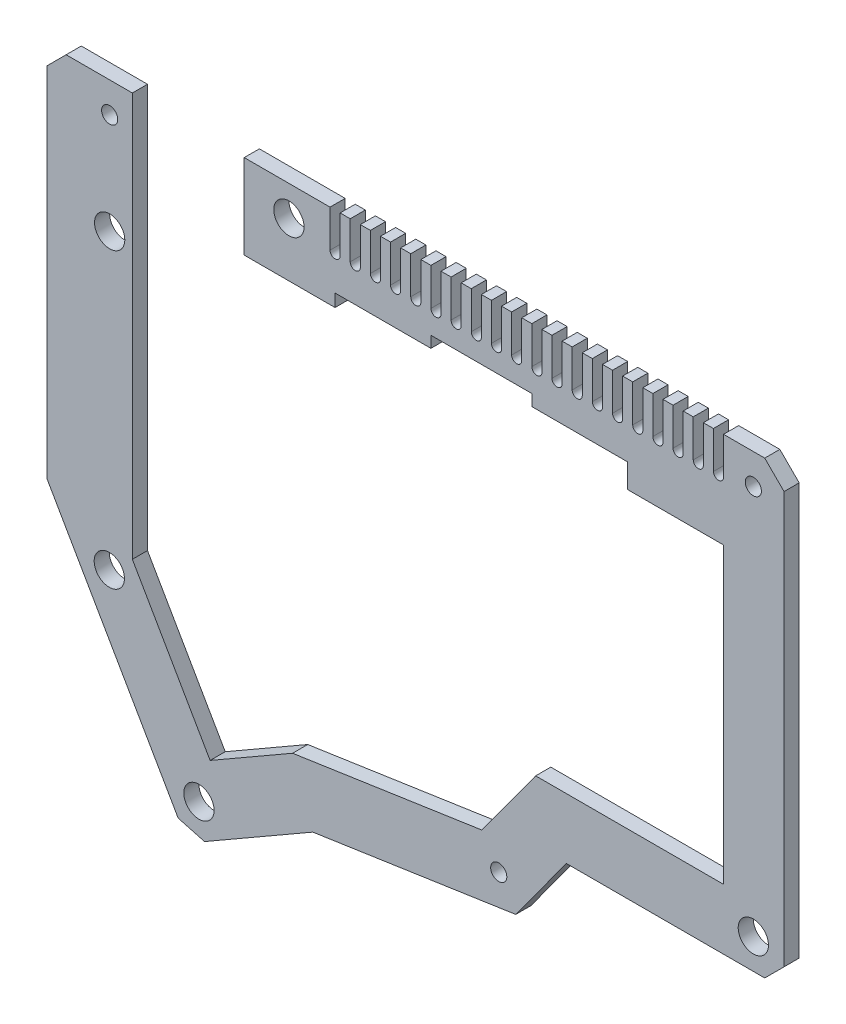
SolidWorks part; units mm, degrees
ref_plane "Plan de face" through (0, 0, 0) normal (0, 0, 1) x (1, 0, 0)
ref_plane "Plan de dessus" through (0, 0, 0) normal (0, 1, 0) x (1, 0, 0)
ref_plane "Plan de droite" through (0, 0, 0) normal (1, 0, 0) x (0, 0, -1)
sketch "Esquisse1" plane through (0, 0, 0) normal (0, 0, 1) x (1, 0, 0)
  line L0 (-117.3419, -15.4198) -> (-103.3409, -15.4198) construction
  line L1 (-103.3409, -15.4198) -> (-103.3409, -29.4208) construction
  line L2 (-103.3409, -29.4208) -> (-117.3419, -29.4208) construction
  line L3 (-117.3419, -29.4208) -> (-117.3419, -15.4198) construction
  line L4 (-98.3406, -27.0457) -> (-98.3406, -13.0447) construction
  line L5 (-98.3406, -13.0447) -> (-84.3396, -13.0447) construction
  line L6 (-84.3396, -13.0447) -> (-84.3396, -27.0457) construction
  line L7 (-84.3396, -27.0457) -> (-98.3406, -27.0457) construction
  line L8 (-79.3392, -24.6705) -> (-79.3392, -10.6695) construction
  line L9 (-79.3392, -10.6695) -> (-65.3382, -10.6695) construction
  line L10 (-65.3382, -10.6695) -> (-65.3382, -24.6705) construction
  line L11 (-65.3382, -24.6705) -> (-79.3392, -24.6705) construction
  line L12 (-60.3379, -27.0457) -> (-60.3379, -13.0447) construction
  line L13 (-60.3379, -13.0447) -> (-46.3369, -13.0447) construction
  line L14 (-46.3369, -13.0447) -> (-46.3369, -27.0457) construction
  line L15 (-46.3369, -27.0457) -> (-60.3379, -27.0457) construction
  line L16 (-41.3365, -31.796) -> (-41.3365, -17.795) construction
  line L17 (-41.3365, -17.795) -> (-27.3355, -17.795) construction
  line L18 (-27.3355, -17.795) -> (-27.3355, -31.796) construction
  line L19 (-27.3355, -31.796) -> (-41.3365, -31.796) construction
  line L20 (-22.3347, -31.796) -> (-22.3347, -17.795) construction
  line L21 (-22.3347, -17.795) -> (-8.3337, -17.795) construction
  line L22 (-8.3337, -17.795) -> (-8.3337, -31.796) construction
  line L23 (-8.3337, -31.796) -> (-22.3347, -31.796) construction
  line L24 (-117.3419, -34.4212) -> (-103.3409, -34.4212) construction
  line L25 (-103.3409, -34.4212) -> (-103.3409, -48.4222) construction
  line L26 (-103.3409, -48.4222) -> (-117.3419, -48.4222) construction
  line L27 (-117.3419, -48.4222) -> (-117.3419, -34.4212) construction
  line L28 (-98.3406, -32.046) -> (-84.3396, -32.046) construction
  line L29 (-84.3396, -32.046) -> (-84.3396, -46.047) construction
  line L30 (-84.3396, -46.047) -> (-98.3406, -46.047) construction
  line L31 (-98.3406, -46.047) -> (-98.3406, -32.046) construction
  line L32 (-79.3392, -29.6709) -> (-65.3382, -29.6709) construction
  line L33 (-65.3382, -29.6709) -> (-65.3382, -43.6718) construction
  line L34 (-65.3382, -43.6718) -> (-79.3392, -43.6718) construction
  line L35 (-79.3392, -43.6718) -> (-79.3392, -29.6709) construction
  line L36 (-60.3379, -32.046) -> (-46.3369, -32.046) construction
  line L37 (-46.3369, -32.046) -> (-46.3369, -46.047) construction
  line L38 (-46.3369, -46.047) -> (-60.3379, -46.047) construction
  line L39 (-60.3379, -46.047) -> (-60.3379, -32.046) construction
  line L40 (-41.3365, -36.7964) -> (-27.3355, -36.7964) construction
  line L41 (-27.3355, -36.7964) -> (-27.3355, -50.7973) construction
  line L42 (-27.3355, -50.7973) -> (-41.3365, -50.7973) construction
  line L43 (-41.3365, -50.7973) -> (-41.3365, -36.7964) construction
  line L44 (-22.3347, -36.7964) -> (-8.3337, -36.7964) construction
  line L45 (-8.3337, -36.7964) -> (-8.3337, -50.7973) construction
  line L46 (-8.3337, -50.7973) -> (-22.3347, -50.7973) construction
  line L47 (-22.3347, -50.7973) -> (-22.3347, -36.7964) construction
  line L48 (-22.3347, -55.7977) -> (-8.3337, -55.7977) construction
  line L49 (-8.3337, -55.7977) -> (-8.3337, -69.7987) construction
  line L50 (-8.3337, -69.7987) -> (-22.3347, -69.7987) construction
  line L51 (-22.3347, -69.7987) -> (-22.3347, -55.7977) construction
  line L52 (-41.3365, -55.7977) -> (-27.3355, -55.7977) construction
  line L53 (-27.3355, -55.7977) -> (-27.3355, -69.7987) construction
  line L54 (-27.3355, -69.7987) -> (-41.3365, -69.7987) construction
  line L55 (-41.3365, -69.7987) -> (-41.3365, -55.7977) construction
  line L56 (-60.3379, -51.0474) -> (-46.3369, -51.0474) construction
  line L57 (-46.3369, -51.0474) -> (-46.3369, -65.0484) construction
  line L58 (-46.3369, -65.0484) -> (-60.3379, -65.0484) construction
  line L59 (-60.3379, -65.0484) -> (-60.3379, -51.0474) construction
  line L60 (-79.3392, -48.6722) -> (-65.3382, -48.6722) construction
  line L61 (-65.3382, -48.6722) -> (-65.3382, -62.6732) construction
  line L62 (-65.3382, -62.6732) -> (-79.3392, -62.6732) construction
  line L63 (-79.3392, -62.6732) -> (-79.3392, -48.6722) construction
  line L64 (-98.3406, -51.0474) -> (-84.3396, -51.0474) construction
  line L65 (-84.3396, -51.0474) -> (-84.3396, -65.0484) construction
  line L66 (-84.3396, -65.0484) -> (-98.3406, -65.0484) construction
  line L67 (-98.3406, -65.0484) -> (-98.3406, -51.0474) construction
  line L68 (-117.3419, -53.4225) -> (-103.3409, -53.4225) construction
  line L69 (-103.3409, -53.4225) -> (-103.3409, -67.4235) construction
  line L70 (-103.3409, -67.4235) -> (-117.3419, -67.4235) construction
  line L71 (-117.3419, -67.4235) -> (-117.3419, -53.4225) construction
  line L72 (-88.8399, -70.6738) -> (-74.8389, -70.6738) construction
  line L73 (-74.8389, -70.6738) -> (-74.8389, -84.6747) construction
  line L74 (-74.8389, -84.6747) -> (-88.8399, -84.6747) construction
  line L75 (-88.8399, -84.6747) -> (-88.8399, -70.6738) construction
  line L76 (-111.4175, -75.4665) -> (-97.8899, -71.8565) construction
  line L77 (-97.8899, -71.8565) -> (-94.28, -85.3841) construction
  line L78 (-94.28, -85.3841) -> (-107.8075, -88.9941) construction
  line L79 (-107.8075, -88.9941) -> (-111.4175, -75.4665) construction
  line L80 (-134.6581, -81.5997) -> (-122.5281, -74.6075) construction
  line L81 (-122.5281, -74.6075) -> (-115.5359, -86.7375) construction
  line L82 (-115.5359, -86.7375) -> (-127.6659, -93.7297) construction
  line L83 (-127.6659, -93.7297) -> (-134.6581, -81.5997) construction
  line L86 (-6.3391, -71.9336) -> (-62.0853, -71.9336) construction
  line L89 (-72.824, -86.6446) -> (-62.0853, -71.9336) construction
  line L96 (-109.7697, -91.4639) -> (-73.0906, -86.6918) construction
  line L97 (-124.664, -99.8297) -> (-110.3971, -91.5881) construction
  line L98 (-139.9408, -76.5013) -> (-126.7151, -99.4281) construction
  line L99 (-119.8527, -15.5421) -> (-139.6028, -15.5421) construction
  line L100 (-100.8528, -13.2921) -> (-118.8527, -13.2921) construction
  line L101 (-63.8455, -8.5421) -> (-80.8528, -8.5421) construction
  line L102 (-44.8455, -10.792) -> (-62.8485, -10.792) construction
  line L103 (-25.8456, -15.5421) -> (-43.8486, -15.5421) construction
  line L104 (-6.8456, -15.5421) -> (-23.8529, -15.5421) construction
  line L105 (-6.2741, -71.3672) -> (-6.2741, -16.1136) construction
  line L106 (-23.8529, -71.9423) -> (-6.8456, -71.9423) construction
  line L107 (-61.8455, -71.9423) -> (-25.8456, -71.9423) construction
  line L108 (-72.6738, -86.4911) -> (-62.1363, -72.0583) construction
  line L109 (-140.1743, -16.1136) -> (-140.1743, -75.5958) construction
  line L110 (-134.3462, 1.5705) -> (-134.3466, -55.7217) construction
  line L111 (-134.3466, -55.7217) -> (-160.479, -70.8411) construction
  line L112 (-160.479, -70.8411) -> (-133.7613, -117.344) construction
  line L113 (-126.937, -119.1852) -> (-105.0783, -106.604) construction
  line L114 (-105.0783, -106.604) -> (-64.4097, -100.5586) construction
  line L115 (-64.4097, -100.5586) -> (-54.4636, -86.9336) construction
  line L116 (3.6609, -86.9336) -> (-54.4636, -86.9336) construction
  line L117 (-10.3391, -81.9326) -> (-10.3391, 1.3161) construction
  line L122 (3.6609, 6.3153) -> (-96.3444, 6.3209) construction
  line L129 (8.6609, -86.9336) -> (8.6609, -0.6796) construction
  line L130 (-48.3431, 6.3182) -> (-96.3444, 6.3209) construction
  line L131 (-115.3458, 1.5705) -> (-134.3462, 1.5705) construction
  line L132 (-160.479, -3.4295) -> (-160.479, -70.8411) construction
  line L134 (-119.3463, 1.5705) -> (-119.3466, -64.3728) construction
  line L135 (-119.3466, -64.3728) -> (-135.695, -73.8315) construction
  line L136 (-140.0228, -71.3355) -> (-140.0228, 1.5705) construction
  line L138 (-160.479, -70.8411) -> (-131.2704, -121.6794) construction
  line L139 (-131.2704, -121.6794) -> (-105.0783, -106.604) construction
  line L140 (-133.7613, -117.344) -> (-126.937, -119.1852) construction
  line L142 (-10.3391, 1.3161) -> (-15.3391, 6.3163) construction
  line L143 (8.6609, -86.9336) -> (-54.4636, -86.9336) construction
  line L144 (-10.3391, -81.9326) -> (-15.3391, -86.9326) construction
  line L147 (-103.3409, 6.3209) -> (-96.3444, 6.3209) construction
  line L148 (-103.3409, 6.3209) -> (-119.3463, 6.3209) construction
  line L149 (-119.3463, 6.3209) -> (-119.3463, 1.5705) construction
  line L150 (-140.0228, 1.5705) -> (-140.0228, 6.3209) construction
  line L151 (-140.0228, 6.3209) -> (-155.479, 6.3209) construction
  line L152 (-160.479, 1.3209) -> (-160.479, -3.4295) construction
  line L153 (-155.479, 6.3209) -> (-160.479, 1.3209) construction
  line L154 (8.6609, -1.685) -> (-119.3463, -1.6779) construction
  line L155 (-146.0924, -79.8227) -> (-128.3223, -110.752) construction
  line L156 (-128.3223, -110.752) -> (-107.7547, -98.9139) construction
  line L157 (-140.0228, -78.3428) -> (-126.1111, -102.5565)
  line L158 (-126.1111, -102.5565) -> (-109.762, -93.1464)
  line L159 (-109.762, -93.1464) -> (-72.2631, -87.5722)
  line L160 (-72.2631, -87.5722) -> (-61.5772, -72.9336)
  line L162 (-24.3391, -72.9336) -> (-24.3391, -14.6796)
  line L164 (-43.3418, -14.6796) -> (-43.3418, -9.9293)
  line L165 (-43.3418, -9.9293) -> (-62.3431, -9.9293)
  line L166 (-62.3431, -9.9293) -> (-62.3431, -7.681)
  line L167 (-62.3431, -7.681) -> (-82.3444, -7.6799)
  line L168 (-82.3444, -7.6799) -> (-82.3444, -9.9293)
  line L169 (-82.3444, -9.9293) -> (-101.3458, -9.9293)
  line L170 (-101.3458, -9.9293) -> (-101.3458, -12.4295)
  line L171 (-101.3458, -12.4295) -> (-119.3464, -12.4295)
  line L172 (-120.3463, -12.4295) -> (-120.3466, -64.3728) construction
  line L173 (-119.8474, -63.5072) -> (-140.5236, -75.4699) construction
  line L174 (-107.7547, -98.9139) -> (-68.8973, -93.1378) construction
  line L175 (-68.8973, -93.1378) -> (-58.5285, -78.9336) construction
  line L176 (0.6609, -78.9336) -> (-58.5285, -78.9336) construction
  line L177 (-18.3391, -78.9336) -> (-18.3391, -1.6845) construction
  line L178 (-62.3428, -1.681) -> (-82.3441, -1.6799) construction
  line L179 (0.6609, -78.9336) -> (0.6609, -14.6796) construction
  line L180 (-146.0228, -76.3355) -> (-146.0228, 1.5705) construction
  line L181 (-140.0228, -76.3355) -> (-140.0228, 1.5705) construction
  line L182 (-135.695, -73.8315) -> (-140.0228, -71.3355) construction
  line L183 (-16.1687, 4.3164) -> (-96.3445, 4.3209)
  line L184 (-103.3409, 4.3209) -> (-96.3445, 4.3209)
  line L185 (-103.3409, 4.3209) -> (-119.3463, 4.3209)
  line L186 (-117.3463, 4.3209) -> (-117.3463, 1.5705) construction
  line L187 (-117.3463, 1.5705) -> (-117.3466, -65.5263) construction
  line L188 (-117.3466, -65.5263) -> (-135.6934, -76.1412) construction
  line L189 (-135.6934, -76.1412) -> (-142.0228, -72.4908) construction
  line L190 (-142.0228, -72.4908) -> (-142.0228, 1.5705) construction
  line L191 (-142.0228, 1.5705) -> (-142.0228, 4.3209) construction
  line L192 (-141.5228, 4.3209) -> (-154.6506, 4.3209)
  line L193 (-154.6506, 4.3209) -> (-158.479, 0.4924)
  line L194 (-158.479, 0.4924) -> (-158.479, -3.4295)
  line L195 (-158.479, -3.4295) -> (-158.479, -70.3075)
  line L196 (-158.479, -70.3075) -> (-132.44, -115.629)
  line L197 (-132.44, -115.629) -> (-127.2163, -117.0383)
  line L198 (-127.2163, -117.0383) -> (-105.7474, -104.6815)
  line L199 (-105.7474, -104.6815) -> (-65.5316, -98.7034)
  line L200 (-65.5316, -98.7034) -> (-55.4798, -84.9336)
  line L201 (-16.1675, -84.9336) -> (-55.4798, -84.9336)
  line L202 (-12.3391, -81.1052) -> (-16.1675, -84.9336)
  line L203 (-12.3391, -81.1052) -> (-12.3391, 0.4866)
  line L204 (-12.3391, 0.4866) -> (-16.1687, 4.3164)
  line L205 (-103.3409, 4.3209) -> (-117.3463, 4.3209) construction
  line L206 (-142.0228, 4.3209) -> (-154.6506, 4.3209) construction
  line L207 (-140.0228, 4.3209) -> (-140.0228, -75.1802) construction
  line L208 (-119.3463, 4.3209) -> (-119.3464, -12.4295)
  line L209 (-140.0228, -78.3428) -> (-140.8899, -76.8336)
  line L210 (-101.3458, -12.4295) -> (-120.3463, -12.4295) construction
  line L211 (-140.8899, -76.8336) -> (-126.1111, -102.5565) construction
  line L217 (-6.3391, -71.9336) -> (-6.3391, -15.6796) construction
  line L220 (-6.3391, -15.6796) -> (-44.3418, -15.6796) construction
  line L221 (-44.3418, -15.6796) -> (-44.3418, -10.9293) construction
  line L222 (-44.3418, -10.9293) -> (-63.3431, -10.9293) construction
  line L223 (-63.3431, -10.9293) -> (-63.3431, -8.681) construction
  line L224 (-63.3431, -8.681) -> (-81.3444, -8.68) construction
  line L225 (-81.3444, -8.68) -> (-81.3444, -10.9293) construction
  line L226 (-81.3444, -10.9293) -> (-100.3458, -10.9293) construction
  line L227 (-100.3458, -10.9293) -> (-100.3458, -13.4295) construction
  line L228 (-100.3458, -13.4295) -> (-119.3463, -13.4295) construction
  line L231 (-119.3463, -13.4295) -> (-119.3466, -64.3728) construction
  line L232 (-119.3466, -64.3728) -> (-140.0228, -76.3355) construction
  line L233 (-140.0228, -76.3355) -> (-125.7426, -101.1906) construction
  line L234 (-125.7426, -101.1906) -> (-110.0965, -92.1851) construction
  line L235 (-110.0965, -92.1851) -> (-72.824, -86.6446) construction
  line L236 (-141.5228, -75.732) -> (-140.8899, -76.8336)
  line L238 (-141.5228, 4.3209) -> (-141.5228, -75.1802)
  line L239 (-141.5228, -75.1802) -> (-141.5228, -75.732)
  line L240 (-5.3391, -72.9336) -> (-5.3391, -14.6796) construction
  line L241 (8.6609, -81.9336) -> (3.6609, -86.9336) construction
  line L242 (6.6609, -81.1052) -> (2.8325, -84.9336) construction
  line L243 (8.6609, -81.9336) -> (8.6609, 1.315) construction
  line L244 (6.6609, -81.1052) -> (6.6609, 0.4866) construction
  line L245 (8.6609, 1.315) -> (3.6609, 6.3153) construction
  line L246 (6.6609, 0.4866) -> (2.8324, 4.3153) construction
  line L247 (-24.3391, -14.6796) -> (-43.3418, -14.6796)
  line L248 (2.8324, 4.3153) -> (-96.3445, 4.3209) construction
  line L249 (-24.3391, -72.9336) -> (-61.5772, -72.9336)
  line L250 (-5.3391, -14.6796) -> (-43.3418, -14.6796) construction
  line L252 (-5.3391, -72.9336) -> (-61.5772, -72.9336) construction
  line L253 (2.8325, -84.9336) -> (-55.4798, -84.9336) construction
  line L328 (-48.3431, 4.0707) -> (-48.3431, 6.3182) construction
  line L329 (-29.3418, 4.0707) -> (-48.3431, 4.0707) construction
  line L330 (-29.3418, -0.6796) -> (-29.3418, 4.0707) construction
  line L331 (8.6609, -0.6796) -> (-29.3418, -0.6796) construction
  line L332 (-115.3458, 4.0707) -> (-115.3458, 1.5705) construction
  line L333 (-96.3444, 4.0707) -> (-115.3458, 4.0707) construction
  line L334 (-96.3444, 6.3209) -> (-96.3444, 4.0707) construction
  circle A2 centre (-18.3391, -1.6845) radius 1.6 construction
  circle A3 centre (-18.3391, -1.6845) radius 3 construction
  circle A4 centre (-110.3971, -1.6784) radius 1.6 construction
  circle A5 centre (-18.3391, -78.9336) radius 1.6 construction
  circle A6 centre (-68.8973, -93.1378) radius 1.6 construction
  circle A7 centre (-128.3223, -110.752) radius 1.6 construction
  circle A8 centre (-146.0924, -79.8227) radius 1.6 construction
  circle A9 centre (-146.0228, -1.6779) radius 1.6 construction
  point P138 (-160.479, 1.5705)
  point P139 (-10.3391, 6.3161)
  point P150 (-160.479, 6.3209)
  dimension "D3" = 3.2
  dimension "D4" = 6
  dimension "D6" = 3.2
  dimension "D7" = 3.2
  dimension "D8" = 3.2
  dimension "D9" = 3.2
  dimension "D10" = 3.2
  dimension "D15" = 3.2
  dimension "D2" = 6
  dimension "D1" = 15
  dimension "D5" = 1
  dimension "D13" = 6
  dimension "D16" = 2
  dimension "D17" = 1.5
extrude "Boss.-Extru.2" add sketch "Esquisse1" along normal blind 3
sketch "Esquisse2" plane through (0, 0, 3) normal (0, 0, 1) x (1, 0, 0)
  line L0 (-12.3391, -3.0693) -> (-25.3391, -3.0693) construction
  line L1 (-12.3391, -81.1052) -> (-12.3391, 0.4866) construction
  line L2 (-25.3391, -3.0693) -> (-25.3391, 4.3169) construction
  line L3 (-29.3391, 4.3169) -> (-29.3391, -3.0693) construction
  line L4 (-16.1687, 4.3164) -> (-96.3445, 4.3209) construction
  line L7 (-25.3391, 4.3169) -> (-25.3391, -3.0693) construction
  line L10 (-24.3391, 4.3169) -> (-24.3391, -3.0693)
  line L13 (-26.3391, 4.3169) -> (-26.3391, -3.0693)
  line L14 (-28.3391, 4.3169) -> (-28.3391, -3.0693)
  line L15 (-30.3391, 4.3169) -> (-30.3391, -3.0693)
  line L16 (-33.3391, 4.3169) -> (-33.3391, -3.0693) construction
  line L17 (-32.3391, 4.3169) -> (-32.3391, -3.0693)
  line L18 (-34.3391, 4.3169) -> (-34.3391, -3.0693)
  line L19 (-37.3391, 4.3169) -> (-37.3391, -3.0693) construction
  line L20 (-36.3391, 4.3169) -> (-36.3391, -3.0693)
  line L21 (-38.3391, 4.3169) -> (-38.3391, -3.0693)
  line L22 (-41.3391, 4.3169) -> (-41.3391, -3.0693) construction
  line L23 (-40.3391, 4.3169) -> (-40.3391, -3.0693)
  line L24 (-42.3391, 4.3169) -> (-42.3391, -3.0693)
  line L25 (-45.3391, 4.3169) -> (-45.3391, -3.0693) construction
  line L26 (-44.3391, 4.3169) -> (-44.3391, -3.0693)
  line L27 (-46.3391, 4.3169) -> (-46.3391, -3.0693)
  line L28 (-49.3391, 4.3169) -> (-49.3391, -3.0693) construction
  line L29 (-48.3391, 4.3169) -> (-48.3391, -3.0693)
  line L30 (-50.3391, 4.3169) -> (-50.3391, -3.0693)
  line L31 (-53.3391, 4.3169) -> (-53.3391, -3.0693) construction
  line L32 (-52.3391, 4.3169) -> (-52.3391, -3.0693)
  line L33 (-54.3391, 4.3169) -> (-54.3391, -3.0693)
  line L34 (-57.3391, 4.3169) -> (-57.3391, -3.0693) construction
  line L35 (-56.3391, 4.3169) -> (-56.3391, -3.0693)
  line L36 (-58.3391, 4.3169) -> (-58.3391, -3.0693)
  line L37 (-61.3391, 4.3169) -> (-61.3391, -3.0693) construction
  line L38 (-60.3391, 4.3169) -> (-60.3391, -3.0693)
  line L39 (-62.3391, 4.3169) -> (-62.3391, -3.0693)
  line L40 (-65.3391, 4.3169) -> (-65.3391, -3.0693) construction
  line L41 (-64.3391, 4.3169) -> (-64.3391, -3.0693)
  line L42 (-66.3391, 4.3169) -> (-66.3391, -3.0693)
  line L43 (-69.3391, 4.3169) -> (-69.3391, -3.0693) construction
  line L44 (-68.3391, 4.3169) -> (-68.3391, -3.0693)
  line L45 (-70.3391, 4.3169) -> (-70.3391, -3.0693)
  line L46 (-73.3391, 4.3169) -> (-73.3391, -3.0693) construction
  line L47 (-72.3391, 4.3169) -> (-72.3391, -3.0693)
  line L48 (-74.3391, 4.3169) -> (-74.3391, -3.0693)
  line L49 (-77.3391, 4.3169) -> (-77.3391, -3.0693) construction
  line L50 (-76.3391, 4.3169) -> (-76.3391, -3.0693)
  line L51 (-78.3391, 4.3169) -> (-78.3391, -3.0693)
  line L52 (-81.3391, 4.3169) -> (-81.3391, -3.0693) construction
  line L53 (-80.3391, 4.3169) -> (-80.3391, -3.0693)
  line L54 (-82.3391, 4.3169) -> (-82.3391, -3.0693)
  line L55 (-85.3391, 4.3169) -> (-85.3391, -3.0693) construction
  line L56 (-84.3391, 4.3169) -> (-84.3391, -3.0693)
  line L57 (-86.3391, 4.3169) -> (-86.3391, -3.0693)
  line L58 (-89.3391, 4.3169) -> (-89.3391, -3.0693) construction
  line L59 (-88.3391, 4.3169) -> (-88.3391, -3.0693)
  line L60 (-90.3391, 4.3169) -> (-90.3391, -3.0693)
  line L61 (-93.3391, 4.3169) -> (-93.3391, -3.0693) construction
  line L62 (-92.3391, 4.3169) -> (-92.3391, -3.0693)
  line L63 (-94.3391, 4.3169) -> (-94.3391, -3.0693)
  line L64 (-97.3391, 4.3169) -> (-97.3391, -3.0693) construction
  line L65 (-96.3391, 4.3169) -> (-96.3391, -3.0693)
  line L66 (-98.3391, 4.3169) -> (-98.3391, -3.0693)
  line L67 (-101.3391, 4.3169) -> (-101.3391, -3.0693) construction
  line L68 (-100.3391, 4.3169) -> (-100.3391, -3.0693)
  line L69 (-102.3391, 4.3169) -> (-102.3391, -3.0693)
  arc A50 (-24.3391, 4.3169) -> (-26.3391, 4.3169) centre (-25.3391, 4.3169) ccw
  arc A51 (-26.3391, -3.0693) -> (-24.3391, -3.0693) centre (-25.3391, -3.0693) ccw
  arc A52 (-28.3391, 4.3169) -> (-30.3391, 4.3169) centre (-29.3391, 4.3169) ccw
  arc A53 (-30.3391, -3.0693) -> (-28.3391, -3.0693) centre (-29.3391, -3.0693) ccw
  arc A54 (-32.3391, 4.3169) -> (-34.3391, 4.3169) centre (-33.3391, 4.3169) ccw
  arc A55 (-34.3391, -3.0693) -> (-32.3391, -3.0693) centre (-33.3391, -3.0693) ccw
  arc A56 (-36.3391, 4.3169) -> (-38.3391, 4.3169) centre (-37.3391, 4.3169) ccw
  arc A57 (-38.3391, -3.0693) -> (-36.3391, -3.0693) centre (-37.3391, -3.0693) ccw
  arc A58 (-40.3391, 4.3169) -> (-42.3391, 4.3169) centre (-41.3391, 4.3169) ccw
  arc A59 (-42.3391, -3.0693) -> (-40.3391, -3.0693) centre (-41.3391, -3.0693) ccw
  arc A60 (-44.3391, 4.3169) -> (-46.3391, 4.3169) centre (-45.3391, 4.3169) ccw
  arc A61 (-46.3391, -3.0693) -> (-44.3391, -3.0693) centre (-45.3391, -3.0693) ccw
  arc A62 (-48.3391, 4.3169) -> (-50.3391, 4.3169) centre (-49.3391, 4.3169) ccw
  arc A63 (-50.3391, -3.0693) -> (-48.3391, -3.0693) centre (-49.3391, -3.0693) ccw
  arc A64 (-52.3391, 4.3169) -> (-54.3391, 4.3169) centre (-53.3391, 4.3169) ccw
  arc A65 (-54.3391, -3.0693) -> (-52.3391, -3.0693) centre (-53.3391, -3.0693) ccw
  arc A66 (-56.3391, 4.3169) -> (-58.3391, 4.3169) centre (-57.3391, 4.3169) ccw
  arc A67 (-58.3391, -3.0693) -> (-56.3391, -3.0693) centre (-57.3391, -3.0693) ccw
  arc A68 (-60.3391, 4.3169) -> (-62.3391, 4.3169) centre (-61.3391, 4.3169) ccw
  arc A69 (-62.3391, -3.0693) -> (-60.3391, -3.0693) centre (-61.3391, -3.0693) ccw
  arc A70 (-64.3391, 4.3169) -> (-66.3391, 4.3169) centre (-65.3391, 4.3169) ccw
  arc A71 (-66.3391, -3.0693) -> (-64.3391, -3.0693) centre (-65.3391, -3.0693) ccw
  arc A72 (-68.3391, 4.3169) -> (-70.3391, 4.3169) centre (-69.3391, 4.3169) ccw
  arc A73 (-70.3391, -3.0693) -> (-68.3391, -3.0693) centre (-69.3391, -3.0693) ccw
  arc A74 (-72.3391, 4.3169) -> (-74.3391, 4.3169) centre (-73.3391, 4.3169) ccw
  arc A75 (-74.3391, -3.0693) -> (-72.3391, -3.0693) centre (-73.3391, -3.0693) ccw
  arc A76 (-76.3391, 4.3169) -> (-78.3391, 4.3169) centre (-77.3391, 4.3169) ccw
  arc A77 (-78.3391, -3.0693) -> (-76.3391, -3.0693) centre (-77.3391, -3.0693) ccw
  arc A78 (-80.3391, 4.3169) -> (-82.3391, 4.3169) centre (-81.3391, 4.3169) ccw
  arc A79 (-82.3391, -3.0693) -> (-80.3391, -3.0693) centre (-81.3391, -3.0693) ccw
  arc A80 (-84.3391, 4.3169) -> (-86.3391, 4.3169) centre (-85.3391, 4.3169) ccw
  arc A81 (-86.3391, -3.0693) -> (-84.3391, -3.0693) centre (-85.3391, -3.0693) ccw
  arc A82 (-88.3391, 4.3169) -> (-90.3391, 4.3169) centre (-89.3391, 4.3169) ccw
  arc A83 (-90.3391, -3.0693) -> (-88.3391, -3.0693) centre (-89.3391, -3.0693) ccw
  arc A84 (-92.3391, 4.3169) -> (-94.3391, 4.3169) centre (-93.3391, 4.3169) ccw
  arc A85 (-94.3391, -3.0693) -> (-92.3391, -3.0693) centre (-93.3391, -3.0693) ccw
  arc A86 (-96.3391, 4.3169) -> (-98.3391, 4.3169) centre (-97.3391, 4.3169) ccw
  arc A87 (-98.3391, -3.0693) -> (-96.3391, -3.0693) centre (-97.3391, -3.0693) ccw
  arc A88 (-100.3391, 4.3169) -> (-102.3391, 4.3169) centre (-101.3391, 4.3169) ccw
  arc A89 (-102.3391, -3.0693) -> (-100.3391, -3.0693) centre (-101.3391, -3.0693) ccw
  point P4 (-25.3391, 0.6238)
  point P14 (-29.3391, 0.6238)
  point P21 (-33.3391, 0.6238)
  point P28 (-37.3391, 0.6238)
  point P35 (-41.3391, 0.6238)
  point P42 (-45.3391, 0.6238)
  point P49 (-49.3391, 0.6238)
  point P56 (-53.3391, 0.6238)
  point P63 (-57.3391, 0.6238)
  point P70 (-61.3391, 0.6238)
  point P77 (-65.3391, 0.6238)
  point P84 (-69.3391, 0.6238)
  point P91 (-73.3391, 0.6238)
  point P98 (-77.3391, 0.6238)
  point P105 (-81.3391, 0.6238)
  point P112 (-85.3391, 0.6238)
  point P119 (-89.3391, 0.6238)
  point P126 (-93.3391, 0.6238)
  point P133 (-97.3391, 0.6238)
  point P140 (-101.3391, 0.6238)
  dimension "D1" = 13
extrude "Enlèv. mat.-Extru.1" cut sketch "Esquisse2" against normal blind 3
sketch "Esquisse3" plane through (0, 0, 0) normal (0, 0, 1) x (1, 0, 0)
  line L96 (-146.0228, -1.6779) -> (-146.0228, -21.6779) construction
  circle A3 centre (-18.4297, -1.6845) radius 3 construction
  circle A10 centre (-110.4876, -1.6784) radius 3
  circle A11 centre (-146.0228, -1.6779) radius 3 construction
  circle A12 centre (-146.0924, -79.8227) radius 3
  circle A13 centre (-128.3223, -110.752) radius 3
  circle A14 centre (-68.8973, -93.1378) radius 3 construction
  circle A15 centre (-18.4297, -78.9336) radius 3
  circle A16 centre (-68.8973, -93.1378) radius 1.6
  circle A17 centre (-146.0228, -1.6779) radius 1.6
  circle A18 centre (-18.4297, -1.6845) radius 1.6
  circle A19 centre (-146.0228, -21.6779) radius 3
  point P89 (-119.3466, -64.3728)
  point P133 (-96.435, 6.3209)
  point P137 (-119.3463, 1.5705)
  point P145 (3.5703, 6.3153)
  point P152 (-119.3463, 6.3209)
  point P158 (-140.8899, -76.8336)
  point P161 (-126.1111, -102.5565)
  point P174 (-101.3458, -12.4295)
  point P175 (-120.3463, -12.4295)
  point P199 (3.1561, 5.3153)
  point P200 (-96.435, 5.3209)
  point P201 (-103.4315, 5.3209)
  dimension "D3" = 3.2
  dimension "D4" = 6
  dimension "D1" = 3.2
  dimension "D2" = 3.2
extrude "Enlèv. mat.-Extru.3" cut sketch "Esquisse3" along normal blind 10
sketch "Esquisse4" plane through (0, 0, 3) normal (0, 0, 1) x (1, 0, 0)
  line L31 (-16.1687, 4.3164) -> (-24.3391, 4.3168)
  line L33 (-16.1687, 4.3164) -> (-24.3391, 4.3168)
  line L35 (-43.3418, -14.6796) -> (-24.3391, -14.6796)
  line L113 (-43.3418, -14.6796) -> (-24.3391, -14.6796)
  line L115 (-24.3391, -72.9336) -> (-61.5772, -72.9336)
  line L117 (-24.3391, -72.9336) -> (-61.5772, -72.9336)
  line L119 (-26.3391, -3.0693) -> (-26.3391, 4.317)
  line L121 (-26.3391, -3.0693) -> (-26.3391, 4.317)
  line L123 (-26.3391, 4.317) -> (-28.3391, 4.3171)
  line L125 (-26.3391, 4.317) -> (-28.3391, 4.3171)
  line L127 (-28.3391, 4.3171) -> (-28.3391, 4.3169)
  line L129 (-28.3391, 4.3171) -> (-28.3391, 4.3169)
  line L131 (-28.3391, 4.3169) -> (-28.3391, -3.0693)
  line L133 (-28.3391, 4.3169) -> (-28.3391, -3.0693)
  line L135 (-30.3391, -3.0693) -> (-30.3391, 4.3169)
  line L137 (-30.3391, -3.0693) -> (-30.3391, 4.3169)
  line L139 (-30.3391, 4.3169) -> (-30.3391, 4.3172)
  line L141 (-30.3391, 4.3169) -> (-30.3391, 4.3172)
  line L143 (-30.3391, 4.3172) -> (-32.3391, 4.3173)
  line L145 (-30.3391, 4.3172) -> (-32.3391, 4.3173)
  line L147 (-32.3391, 4.3173) -> (-32.3391, 4.3169)
  line L149 (-32.3391, 4.3173) -> (-32.3391, 4.3169)
  line L151 (-32.3391, 4.3169) -> (-32.3391, -3.0693)
  line L153 (-32.3391, 4.3169) -> (-32.3391, -3.0693)
  line L155 (-34.3391, -3.0693) -> (-34.3391, 4.3169)
  line L157 (-34.3391, -3.0693) -> (-34.3391, 4.3169)
  line L159 (-34.3391, 4.3169) -> (-34.3391, 4.3174)
  line L161 (-34.3391, 4.3169) -> (-34.3391, 4.3174)
  line L163 (-34.3391, 4.3174) -> (-36.3391, 4.3175)
  line L165 (-34.3391, 4.3174) -> (-36.3391, 4.3175)
  line L167 (-36.3391, 4.3175) -> (-36.3391, 4.3169)
  line L169 (-36.3391, 4.3175) -> (-36.3391, 4.3169)
  line L171 (-36.3391, 4.3169) -> (-36.3391, -3.0693)
  line L173 (-36.3391, 4.3169) -> (-36.3391, -3.0693)
  line L175 (-38.3391, -3.0693) -> (-38.3391, 4.3169)
  line L176 (-38.3391, -3.0693) -> (-38.3391, 4.3169)
  line L178 (-38.3391, 4.3169) -> (-38.3391, 4.3176)
  line L180 (-38.3391, 4.3169) -> (-38.3391, 4.3176)
  line L182 (-38.3391, 4.3176) -> (-40.3391, 4.3177)
  line L183 (-119.3463, 4.3209) -> (-119.3464, -12.4295)
  line L184 (-119.3464, -12.4295) -> (-101.3458, -12.4295)
  line L185 (-101.3458, -12.4295) -> (-101.3458, -9.9293)
  line L186 (-101.3458, -9.9293) -> (-82.3444, -9.9293)
  line L187 (-82.3444, -9.9293) -> (-82.3444, -7.6799)
  line L188 (-82.3444, -7.6799) -> (-62.3431, -7.681)
  line L189 (-62.3431, -7.681) -> (-62.3431, -9.9293)
  line L190 (-62.3431, -9.9293) -> (-43.3418, -9.9293)
  line L191 (-43.3418, -9.9293) -> (-43.3418, -14.6796)
  line L193 (-24.3391, -14.6796) -> (-24.3391, -72.9336)
  line L194 (-38.3391, 4.3176) -> (-40.3391, 4.3177)
  line L195 (-61.5772, -72.9336) -> (-72.2631, -87.5722)
  line L196 (-72.2631, -87.5722) -> (-109.762, -93.1464)
  line L197 (-109.762, -93.1464) -> (-126.1111, -102.5565)
  line L198 (-126.1111, -102.5565) -> (-141.5228, -75.732)
  line L199 (-141.5228, -75.732) -> (-141.5228, 4.3209)
  line L200 (-141.5228, 4.3209) -> (-154.6506, 4.3209)
  line L201 (-154.6506, 4.3209) -> (-158.479, 0.4924)
  line L202 (-158.479, 0.4924) -> (-158.479, -70.3075)
  line L203 (-158.479, -70.3075) -> (-132.44, -115.629)
  line L204 (-132.44, -115.629) -> (-127.2163, -117.0383)
  line L205 (-127.2163, -117.0383) -> (-105.7474, -104.6815)
  line L206 (-105.7474, -104.6815) -> (-65.5316, -98.7034)
  line L207 (-65.5316, -98.7034) -> (-55.4798, -84.9336)
  line L208 (-55.4798, -84.9336) -> (-16.1675, -84.9336)
  line L209 (-16.1675, -84.9336) -> (-12.3391, -81.1052)
  line L210 (-12.3391, -81.1052) -> (-12.3391, 0.4866)
  line L211 (-12.3391, 0.4866) -> (-16.1687, 4.3164)
  line L289 (-119.3463, 4.3209) -> (-119.3464, -12.4295)
  line L290 (-119.3464, -12.4295) -> (-101.3458, -12.4295)
  line L291 (-101.3458, -12.4295) -> (-101.3458, -9.9293)
  line L292 (-101.3458, -9.9293) -> (-82.3444, -9.9293)
  line L293 (-82.3444, -9.9293) -> (-82.3444, -7.6799)
  line L294 (-82.3444, -7.6799) -> (-62.3431, -7.681)
  line L295 (-62.3431, -7.681) -> (-62.3431, -9.9293)
  line L296 (-62.3431, -9.9293) -> (-43.3418, -9.9293)
  line L297 (-43.3418, -9.9293) -> (-43.3418, -14.6796)
  line L299 (-24.3391, -14.6796) -> (-24.3391, -72.9336)
  line L301 (-61.5772, -72.9336) -> (-72.2631, -87.5722)
  line L302 (-72.2631, -87.5722) -> (-109.762, -93.1464)
  line L303 (-109.762, -93.1464) -> (-126.1111, -102.5565)
  line L304 (-126.1111, -102.5565) -> (-141.5228, -75.732)
  line L305 (-141.5228, -75.732) -> (-141.5228, 4.3209)
  line L306 (-141.5228, 4.3209) -> (-154.6506, 4.3209)
  line L307 (-154.6506, 4.3209) -> (-158.479, 0.4924)
  line L308 (-158.479, 0.4924) -> (-158.479, -70.3075)
  line L309 (-158.479, -70.3075) -> (-132.44, -115.629)
  line L310 (-132.44, -115.629) -> (-127.2163, -117.0383)
  line L311 (-127.2163, -117.0383) -> (-105.7474, -104.6815)
  line L312 (-105.7474, -104.6815) -> (-65.5316, -98.7034)
  line L313 (-65.5316, -98.7034) -> (-55.4798, -84.9336)
  line L314 (-55.4798, -84.9336) -> (-16.1675, -84.9336)
  line L315 (-16.1675, -84.9336) -> (-12.3391, -81.1052)
  line L316 (-12.3391, -81.1052) -> (-12.3391, 0.4866)
  line L317 (-12.3391, 0.4866) -> (-16.1687, 4.3164)
  line L319 (-40.3391, 4.3177) -> (-40.3391, 4.3169)
  line L321 (-40.3391, 4.3177) -> (-40.3391, 4.3169)
  line L323 (-40.3391, 4.3169) -> (-40.3391, -3.0693)
  line L325 (-40.3391, 4.3169) -> (-40.3391, -3.0693)
  line L327 (-42.3391, -3.0693) -> (-42.3391, 4.3169)
  line L329 (-42.3391, -3.0693) -> (-42.3391, 4.3169)
  line L331 (-42.3391, 4.3169) -> (-42.3391, 4.3178)
  line L333 (-42.3391, 4.3169) -> (-42.3391, 4.3178)
  line L335 (-42.3391, 4.3178) -> (-44.3391, 4.318)
  line L337 (-42.3391, 4.3178) -> (-44.3391, 4.318)
  line L339 (-44.3391, 4.318) -> (-44.3391, 4.3169)
  line L341 (-44.3391, 4.318) -> (-44.3391, 4.3169)
  line L343 (-44.3391, 4.3169) -> (-44.3391, -3.0693)
  line L345 (-44.3391, 4.3169) -> (-44.3391, -3.0693)
  line L347 (-46.3391, -3.0693) -> (-46.3391, 4.3169)
  line L349 (-46.3391, -3.0693) -> (-46.3391, 4.3169)
  line L351 (-46.3391, 4.3169) -> (-46.3391, 4.3181)
  line L353 (-46.3391, 4.3169) -> (-46.3391, 4.3181)
  line L355 (-46.3391, 4.3181) -> (-48.3391, 4.3182)
  line L357 (-46.3391, 4.3181) -> (-48.3391, 4.3182)
  line L359 (-48.3391, 4.3182) -> (-48.3391, 4.3169)
  line L361 (-48.3391, 4.3182) -> (-48.3391, 4.3169)
  line L363 (-48.3391, 4.3169) -> (-48.3391, -3.0693)
  line L365 (-48.3391, 4.3169) -> (-48.3391, -3.0693)
  line L367 (-50.3391, -3.0693) -> (-50.3391, 4.3169)
  line L369 (-50.3391, -3.0693) -> (-50.3391, 4.3169)
  line L371 (-50.3391, 4.3169) -> (-50.3391, 4.3183)
  line L373 (-50.3391, 4.3169) -> (-50.3391, 4.3183)
  line L375 (-50.3391, 4.3183) -> (-52.3391, 4.3184)
  line L377 (-50.3391, 4.3183) -> (-52.3391, 4.3184)
  line L379 (-52.3391, 4.3184) -> (-52.3391, 4.3169)
  line L381 (-52.3391, 4.3184) -> (-52.3391, 4.3169)
  line L383 (-52.3391, 4.3169) -> (-52.3391, -3.0693)
  line L385 (-52.3391, 4.3169) -> (-52.3391, -3.0693)
  line L387 (-54.3391, -3.0693) -> (-54.3391, 4.3169)
  line L389 (-54.3391, -3.0693) -> (-54.3391, 4.3169)
  line L391 (-54.3391, 4.3169) -> (-54.3391, 4.3185)
  line L393 (-102.3391, 4.3209) -> (-119.3463, 4.3209)
  line L394 (-102.3391, 4.3209) -> (-119.3463, 4.3209)
  line L395 (-54.3391, 4.3169) -> (-54.3391, 4.3185)
  line L397 (-54.3391, 4.3185) -> (-56.3391, 4.3186)
  line L421 (-54.3391, 4.3185) -> (-56.3391, 4.3186)
  line L422 (-56.3391, 4.3186) -> (-56.3391, 4.3169)
  line L423 (-56.3391, 4.3186) -> (-56.3391, 4.3169)
  line L424 (-56.3391, 4.3169) -> (-56.3391, -3.0693)
  line L425 (-56.3391, 4.3169) -> (-56.3391, -3.0693)
  line L426 (-58.3391, -3.0693) -> (-58.3391, 4.3169)
  line L427 (-58.3391, -3.0693) -> (-58.3391, 4.3169)
  line L428 (-58.3391, 4.3169) -> (-58.3391, 4.3187)
  line L429 (-58.3391, 4.3169) -> (-58.3391, 4.3187)
  line L430 (-58.3391, 4.3187) -> (-60.3391, 4.3188)
  line L431 (-58.3391, 4.3187) -> (-60.3391, 4.3188)
  line L432 (-60.3391, 4.3188) -> (-60.3391, 4.3169)
  line L433 (-60.3391, 4.3188) -> (-60.3391, 4.3169)
  line L434 (-60.3391, 4.3169) -> (-60.3391, -3.0693)
  line L435 (-60.3391, 4.3169) -> (-60.3391, -3.0693)
  line L436 (-62.3391, -3.0693) -> (-62.3391, 4.3169)
  line L437 (-62.3391, -3.0693) -> (-62.3391, 4.3169)
  line L438 (-62.3391, 4.3169) -> (-62.3391, 4.319)
  line L439 (-62.3391, 4.3169) -> (-62.3391, 4.319)
  line L440 (-62.3391, 4.319) -> (-64.3391, 4.3191)
  line L441 (-62.3391, 4.319) -> (-64.3391, 4.3191)
  line L442 (-64.3391, 4.3191) -> (-64.3391, 4.3169)
  line L443 (-64.3391, 4.3191) -> (-64.3391, 4.3169)
  line L444 (-64.3391, 4.3169) -> (-64.3391, -3.0693)
  line L445 (-64.3391, 4.3169) -> (-64.3391, -3.0693)
  line L446 (-66.3391, -3.0693) -> (-66.3391, 4.3169)
  line L447 (-66.3391, -3.0693) -> (-66.3391, 4.3169)
  line L448 (-66.3391, 4.3169) -> (-66.3391, 4.3192)
  line L449 (-66.3391, 4.3169) -> (-66.3391, 4.3192)
  line L450 (-66.3391, 4.3192) -> (-68.3391, 4.3193)
  line L451 (-66.3391, 4.3192) -> (-68.3391, 4.3193)
  line L452 (-68.3391, 4.3193) -> (-68.3391, 4.3169)
  line L453 (-68.3391, 4.3193) -> (-68.3391, 4.3169)
  line L454 (-68.3391, 4.3169) -> (-68.3391, -3.0693)
  line L455 (-68.3391, 4.3169) -> (-68.3391, -3.0693)
  line L456 (-70.3391, -3.0693) -> (-70.3391, 4.3169)
  line L457 (-70.3391, -3.0693) -> (-70.3391, 4.3169)
  line L458 (-70.3391, 4.3169) -> (-70.3391, 4.3194)
  line L459 (-70.3391, 4.3169) -> (-70.3391, 4.3194)
  line L460 (-70.3391, 4.3194) -> (-72.3391, 4.3195)
  line L461 (-70.3391, 4.3194) -> (-72.3391, 4.3195)
  line L462 (-72.3391, 4.3195) -> (-72.3391, 4.3169)
  line L463 (-72.3391, 4.3195) -> (-72.3391, 4.3169)
  line L464 (-72.3391, 4.3169) -> (-72.3391, -3.0693)
  line L465 (-72.3391, 4.3169) -> (-72.3391, -3.0693)
  line L466 (-74.3391, -3.0693) -> (-74.3391, 4.3169)
  line L467 (-74.3391, -3.0693) -> (-74.3391, 4.3169)
  line L468 (-74.3391, 4.3169) -> (-74.3391, 4.3196)
  line L469 (-74.3391, 4.3169) -> (-74.3391, 4.3196)
  line L470 (-74.3391, 4.3196) -> (-76.3391, 4.3197)
  line L471 (-74.3391, 4.3196) -> (-76.3391, 4.3197)
  line L472 (-76.3391, 4.3197) -> (-76.3391, 4.3169)
  line L473 (-76.3391, 4.3197) -> (-76.3391, 4.3169)
  line L474 (-76.3391, 4.3169) -> (-76.3391, -3.0693)
  line L475 (-76.3391, 4.3169) -> (-76.3391, -3.0693)
  line L476 (-78.3391, -3.0693) -> (-78.3391, 4.3169)
  line L477 (-78.3391, -3.0693) -> (-78.3391, 4.3169)
  line L478 (-78.3391, 4.3169) -> (-78.3391, 4.3199)
  line L479 (-78.3391, 4.3169) -> (-78.3391, 4.3199)
  line L480 (-78.3391, 4.3199) -> (-80.3391, 4.32)
  line L481 (-78.3391, 4.3199) -> (-80.3391, 4.32)
  line L482 (-80.3391, 4.32) -> (-80.3391, 4.3169)
  line L483 (-80.3391, 4.32) -> (-80.3391, 4.3169)
  line L484 (-80.3391, 4.3169) -> (-80.3391, -3.0693)
  line L485 (-80.3391, 4.3169) -> (-80.3391, -3.0693)
  line L486 (-82.3391, -3.0693) -> (-82.3391, 4.3169)
  line L487 (-82.3391, -3.0693) -> (-82.3391, 4.3169)
  line L488 (-82.3391, 4.3169) -> (-82.3391, 4.3201)
  line L489 (-82.3391, 4.3169) -> (-82.3391, 4.3201)
  line L490 (-82.3391, 4.3201) -> (-84.3391, 4.3202)
  line L491 (-82.3391, 4.3201) -> (-84.3391, 4.3202)
  line L492 (-84.3391, 4.3202) -> (-84.3391, 4.3169)
  line L493 (-84.3391, 4.3202) -> (-84.3391, 4.3169)
  line L494 (-84.3391, 4.3169) -> (-84.3391, -3.0693)
  line L495 (-84.3391, 4.3169) -> (-84.3391, -3.0693)
  line L496 (-86.3391, -3.0693) -> (-86.3391, 4.3169)
  line L497 (-86.3391, -3.0693) -> (-86.3391, 4.3169)
  line L498 (-86.3391, 4.3169) -> (-86.3391, 4.3203)
  line L499 (-86.3391, 4.3169) -> (-86.3391, 4.3203)
  line L500 (-86.3391, 4.3203) -> (-88.3391, 4.3204)
  line L501 (-86.3391, 4.3203) -> (-88.3391, 4.3204)
  line L502 (-88.3391, 4.3204) -> (-88.3391, 4.3169)
  line L503 (-88.3391, 4.3204) -> (-88.3391, 4.3169)
  line L504 (-88.3391, 4.3169) -> (-88.3391, -3.0693)
  line L505 (-88.3391, 4.3169) -> (-88.3391, -3.0693)
  line L506 (-90.3391, -3.0693) -> (-90.3391, 4.3169)
  line L507 (-90.3391, -3.0693) -> (-90.3391, 4.3169)
  line L508 (-90.3391, 4.3169) -> (-90.3391, 4.3205)
  line L509 (-90.3391, 4.3169) -> (-90.3391, 4.3205)
  line L510 (-90.3391, 4.3205) -> (-92.3391, 4.3206)
  line L511 (-90.3391, 4.3205) -> (-92.3391, 4.3206)
  line L512 (-92.3391, 4.3206) -> (-92.3391, 4.3169)
  line L513 (-92.3391, 4.3206) -> (-92.3391, 4.3169)
  line L514 (-92.3391, 4.3169) -> (-92.3391, -3.0693)
  line L515 (-92.3391, 4.3169) -> (-92.3391, -3.0693)
  line L516 (-94.3391, -3.0693) -> (-94.3391, 4.3169)
  line L517 (-94.3391, -3.0693) -> (-94.3391, 4.3169)
  line L518 (-94.3391, 4.3169) -> (-94.3391, 4.3207)
  line L519 (-94.3391, 4.3169) -> (-94.3391, 4.3207)
  line L520 (-94.3391, 4.3207) -> (-96.3391, 4.3209)
  line L521 (-94.3391, 4.3207) -> (-96.3391, 4.3209)
  line L522 (-96.3391, 4.3209) -> (-96.3391, 4.3169)
  line L523 (-96.3391, 4.3209) -> (-96.3391, 4.3169)
  line L524 (-96.3391, 4.3169) -> (-96.3391, -3.0693)
  line L525 (-96.3391, 4.3169) -> (-96.3391, -3.0693)
  line L526 (-98.3391, -3.0693) -> (-98.3391, 4.3169)
  line L527 (-98.3391, -3.0693) -> (-98.3391, 4.3169)
  line L528 (-98.3391, 4.3169) -> (-98.3391, 4.3209)
  line L529 (-98.3391, 4.3169) -> (-98.3391, 4.3209)
  line L530 (-98.3391, 4.3209) -> (-100.3391, 4.3209)
  line L531 (-98.3391, 4.3209) -> (-100.3391, 4.3209)
  line L532 (-100.3391, 4.3209) -> (-100.3391, 4.3169)
  line L533 (-100.3391, 4.3209) -> (-100.3391, 4.3169)
  line L534 (-100.3391, 4.3169) -> (-100.3391, -3.0693)
  line L535 (-100.3391, 4.3169) -> (-100.3391, -3.0693)
  line L536 (-102.3391, -3.0693) -> (-102.3391, 4.3169)
  line L537 (-102.3391, -3.0693) -> (-102.3391, 4.3169)
  line L538 (-102.3391, 4.3169) -> (-102.3391, 4.3209)
  line L539 (-102.3391, 4.3169) -> (-102.3391, 4.3209)
  line L540 (-24.3391, 4.3168) -> (-24.3391, -3.0693)
  line L541 (-24.3391, 4.3168) -> (-24.3391, -3.0693)
  circle A0 centre (-146.0228, -1.6779) radius 1.6 construction
  circle A1 centre (-146.0228, -21.6779) radius 3 construction
  circle A2 centre (-146.0924, -79.8227) radius 3 construction
  circle A3 centre (-128.3223, -110.752) radius 3 construction
  circle A4 centre (-68.8973, -93.1378) radius 1.6 construction
  circle A5 centre (-110.4876, -1.6784) radius 3 construction
  circle A6 centre (-18.4297, -1.6845) radius 1.6 construction
  circle A7 centre (-18.4297, -78.9336) radius 3 construction
  circle A8 centre (-146.0228, -1.6779) radius 1.6
  circle A9 centre (-146.0228, -21.6779) radius 3
  circle A10 centre (-146.0924, -79.8227) radius 3
  circle A11 centre (-128.3223, -110.752) radius 3
  circle A12 centre (-68.8973, -93.1378) radius 1.6
  circle A13 centre (-110.4876, -1.6784) radius 3
  circle A14 centre (-18.4297, -1.6845) radius 1.6
  circle A15 centre (-18.4297, -78.9336) radius 3
  arc A36 (-30.3391, -3.0693) -> (-28.3391, -3.0693) centre (-29.3391, -3.0693) ccw
  arc A37 (-30.3391, -3.0693) -> (-28.3391, -3.0693) centre (-29.3391, -3.0693) ccw
  arc A38 (-34.3391, -3.0693) -> (-32.3391, -3.0693) centre (-33.3391, -3.0693) ccw
  arc A39 (-34.3391, -3.0693) -> (-32.3391, -3.0693) centre (-33.3391, -3.0693) ccw
  arc A40 (-38.3391, -3.0693) -> (-36.3391, -3.0693) centre (-37.3391, -3.0693) ccw
  arc A41 (-38.3391, -3.0693) -> (-36.3391, -3.0693) centre (-37.3391, -3.0693) ccw
  arc A43 (-42.3391, -3.0693) -> (-40.3391, -3.0693) centre (-41.3391, -3.0693) ccw
  arc A45 (-42.3391, -3.0693) -> (-40.3391, -3.0693) centre (-41.3391, -3.0693) ccw
  arc A47 (-46.3391, -3.0693) -> (-44.3391, -3.0693) centre (-45.3391, -3.0693) ccw
  arc A49 (-46.3391, -3.0693) -> (-44.3391, -3.0693) centre (-45.3391, -3.0693) ccw
  arc A76 (-50.3391, -3.0693) -> (-48.3391, -3.0693) centre (-49.3391, -3.0693) ccw
  arc A78 (-50.3391, -3.0693) -> (-48.3391, -3.0693) centre (-49.3391, -3.0693) ccw
  arc A80 (-54.3391, -3.0693) -> (-52.3391, -3.0693) centre (-53.3391, -3.0693) ccw
  arc A82 (-54.3391, -3.0693) -> (-52.3391, -3.0693) centre (-53.3391, -3.0693) ccw
  arc A84 (-58.3391, -3.0693) -> (-56.3391, -3.0693) centre (-57.3391, -3.0693) ccw
  arc A86 (-58.3391, -3.0693) -> (-56.3391, -3.0693) centre (-57.3391, -3.0693) ccw
  arc A88 (-62.3391, -3.0693) -> (-60.3391, -3.0693) centre (-61.3391, -3.0693) ccw
  arc A90 (-62.3391, -3.0693) -> (-60.3391, -3.0693) centre (-61.3391, -3.0693) ccw
  arc A92 (-66.3391, -3.0693) -> (-64.3391, -3.0693) centre (-65.3391, -3.0693) ccw
  arc A94 (-66.3391, -3.0693) -> (-64.3391, -3.0693) centre (-65.3391, -3.0693) ccw
  arc A96 (-70.3391, -3.0693) -> (-68.3391, -3.0693) centre (-69.3391, -3.0693) ccw
  arc A98 (-70.3391, -3.0693) -> (-68.3391, -3.0693) centre (-69.3391, -3.0693) ccw
  arc A100 (-74.3391, -3.0693) -> (-72.3391, -3.0693) centre (-73.3391, -3.0693) ccw
  arc A102 (-74.3391, -3.0693) -> (-72.3391, -3.0693) centre (-73.3391, -3.0693) ccw
  arc A104 (-78.3391, -3.0693) -> (-76.3391, -3.0693) centre (-77.3391, -3.0693) ccw
  arc A106 (-78.3391, -3.0693) -> (-76.3391, -3.0693) centre (-77.3391, -3.0693) ccw
  arc A108 (-82.3391, -3.0693) -> (-80.3391, -3.0693) centre (-81.3391, -3.0693) ccw
  arc A110 (-82.3391, -3.0693) -> (-80.3391, -3.0693) centre (-81.3391, -3.0693) ccw
  arc A112 (-86.3391, -3.0693) -> (-84.3391, -3.0693) centre (-85.3391, -3.0693) ccw
  arc A114 (-86.3391, -3.0693) -> (-84.3391, -3.0693) centre (-85.3391, -3.0693) ccw
  arc A116 (-90.3391, -3.0693) -> (-88.3391, -3.0693) centre (-89.3391, -3.0693) ccw
  arc A117 (-90.3391, -3.0693) -> (-88.3391, -3.0693) centre (-89.3391, -3.0693) ccw
  arc A118 (-94.3391, -3.0693) -> (-92.3391, -3.0693) centre (-93.3391, -3.0693) ccw
  arc A119 (-94.3391, -3.0693) -> (-92.3391, -3.0693) centre (-93.3391, -3.0693) ccw
  arc A120 (-98.3391, -3.0693) -> (-96.3391, -3.0693) centre (-97.3391, -3.0693) ccw
  arc A121 (-98.3391, -3.0693) -> (-96.3391, -3.0693) centre (-97.3391, -3.0693) ccw
  arc A122 (-102.3391, -3.0693) -> (-100.3391, -3.0693) centre (-101.3391, -3.0693) ccw
  arc A123 (-102.3391, -3.0693) -> (-100.3391, -3.0693) centre (-101.3391, -3.0693) ccw
  arc A124 (-26.3391, -3.0693) -> (-24.3391, -3.0693) centre (-25.3391, -3.0693) ccw
  arc A125 (-26.3391, -3.0693) -> (-24.3391, -3.0693) centre (-25.3391, -3.0693) ccw
  dimension "D1" = 0
